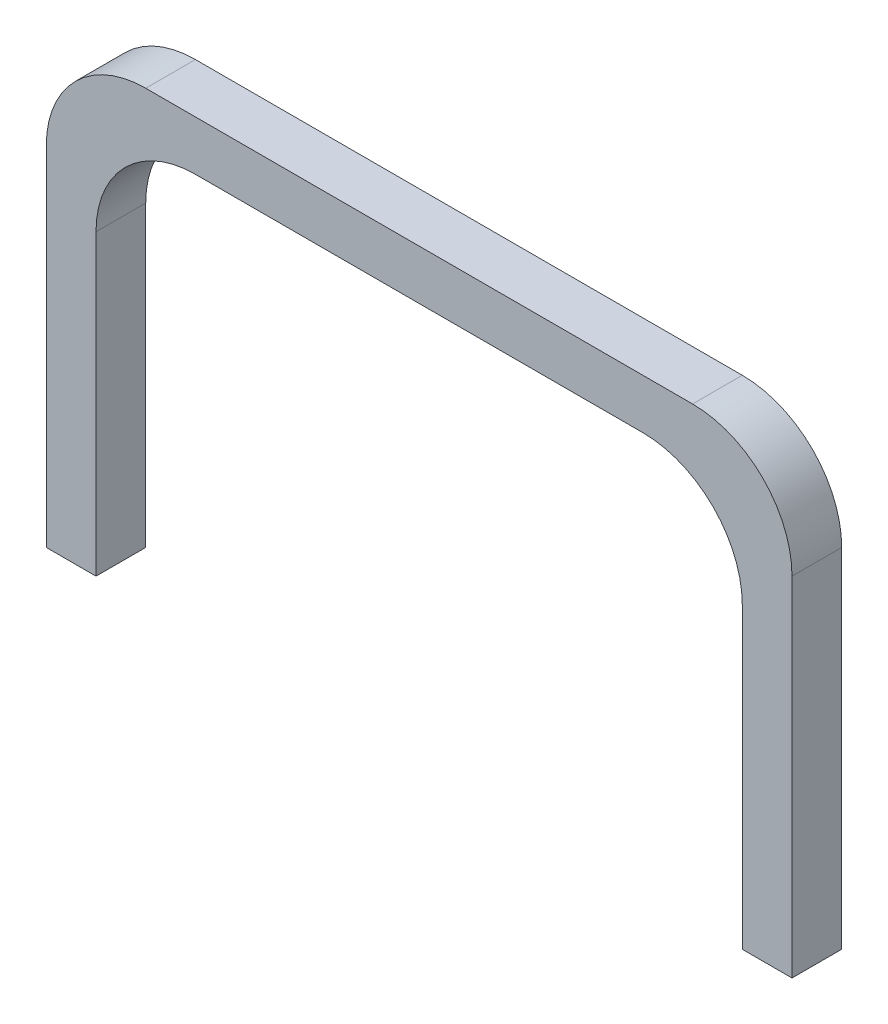
SolidWorks part; units mm, degrees
ref_plane "Спереди" through (0, 0, 0) normal (0, 0, 1) x (1, 0, 0)
ref_plane "Сверху" through (0, 0, 0) normal (0, 1, 0) x (1, 0, 0)
ref_plane "Справа" through (0, 0, 0) normal (1, 0, 0) x (0, 0, -1)
sketch "Эскиз1" plane through (0, 0, 0) normal (0, 1, 0) x (1, 0, 0)
  line L1 (-7.5, 0.5) -> (7.5, 0.5)
  line L2 (-7.5, 0.5) -> (-7.5, -0.5)
  line L3 (-7.5, -0.5) -> (7.5, -0.5)
  line L4 (7.5, 0.5) -> (7.5, -0.5)
  line L5 (0, -0.5) -> (0, 0.5) construction
  line L6 (-7.5, 0) -> (7.5, 0) construction
  point P0 (0, 0)
  dimension "D1" = 15
  dimension "D2" = 1
extrude "Бобышка-Вытянуть1" add sketch "Эскиз1" along normal mid plane 1
sketch "Эскиз2" plane through (0, -0.5, 0) normal (0, -1, 0) x (1, 0, 0)
  line L0 (7.5, -0.5) -> (-7.5, -0.5) construction
  line L1 (-7.5, 0.5) -> (-6.5, 0.5)
  line L2 (-7.5, 0.5) -> (-7.5, -0.5)
  line L3 (-7.5, -0.5) -> (-6.5, -0.5)
  line L4 (-6.5, 0.5) -> (-6.5, -0.5)
  line L5 (0, 1.285) -> (0, -1.392) construction
  line L6 (6.5, 0.5) -> (6.5, -0.5)
  line L7 (7.5, -0.5) -> (6.5, -0.5)
  line L8 (7.5, 0.5) -> (7.5, -0.5)
  line L9 (7.5, 0.5) -> (6.5, 0.5)
  dimension "D1" = 1
extrude "Бобышка-Вытянуть2" add sketch "Эскиз2" along normal blind 8
fillet "Скругление1" radius 2 4 edges at (7.5, 0.5, 0) (-7.5, 0.5, 0) (6.5, -0.5, 0) (-6.5, -0.5, 0)
